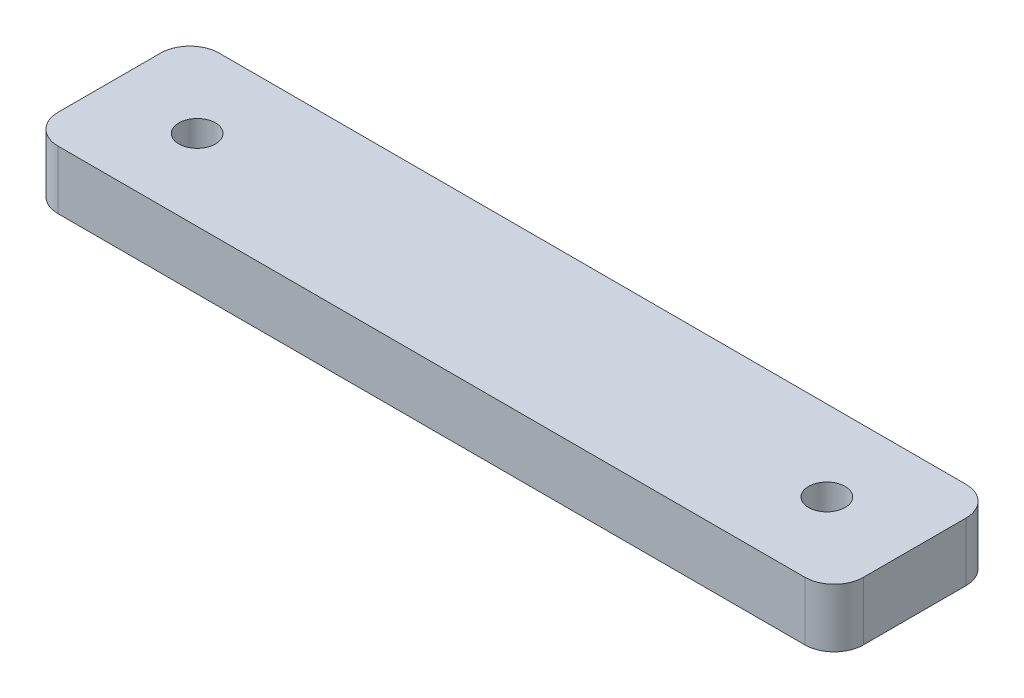
SolidWorks part; units mm, degrees
ref_plane "Front" through (0, 0, 0) normal (0, 0, 1) x (1, 0, 0)
ref_plane "Top" through (0, 0, 0) normal (0, 1, 0) x (1, 0, 0)
ref_plane "Right" through (0, 0, 0) normal (1, 0, 0) x (0, 0, -1)
sketch "Croquis1" plane through (0, 0, 0) normal (0, 1, 0) x (1, 0, 0)
  line L0 (-72.6012, 0) -> (3557.4579, 0) construction
  line L1 (0, -72.6012) -> (0, 3557.4579) construction
  line L3 (-13.75, -2.75) -> (13.75, -2.75)
  line L4 (-13.75, -2.75) -> (-13.75, 2.75)
  line L5 (-13.75, 2.75) -> (13.75, 2.75)
  line L6 (13.75, -2.75) -> (13.75, 2.75)
  line L7 (-13.75, -2.75) -> (13.75, 2.75) construction
  line L8 (-13.75, 2.75) -> (13.75, -2.75) construction
  circle A0 centre (-10.75, 0) radius 0.625
  circle A1 centre (10.75, 0) radius 0.625
  point P4 (0, 0)
  dimension "D3" = 1.25
  dimension "D4" = 3
  dimension "D1" = 5.5
  dimension "D2" = 27.5
extrude "Saliente-Extruir1" add sketch "Croquis1" along normal blind 2
fillet "Redondeo1" radius 1 4 edges at (13.75, 1, 2.75) (13.75, 1, -2.75) (-13.75, 1, -2.75) (-13.75, 1, 2.75)
